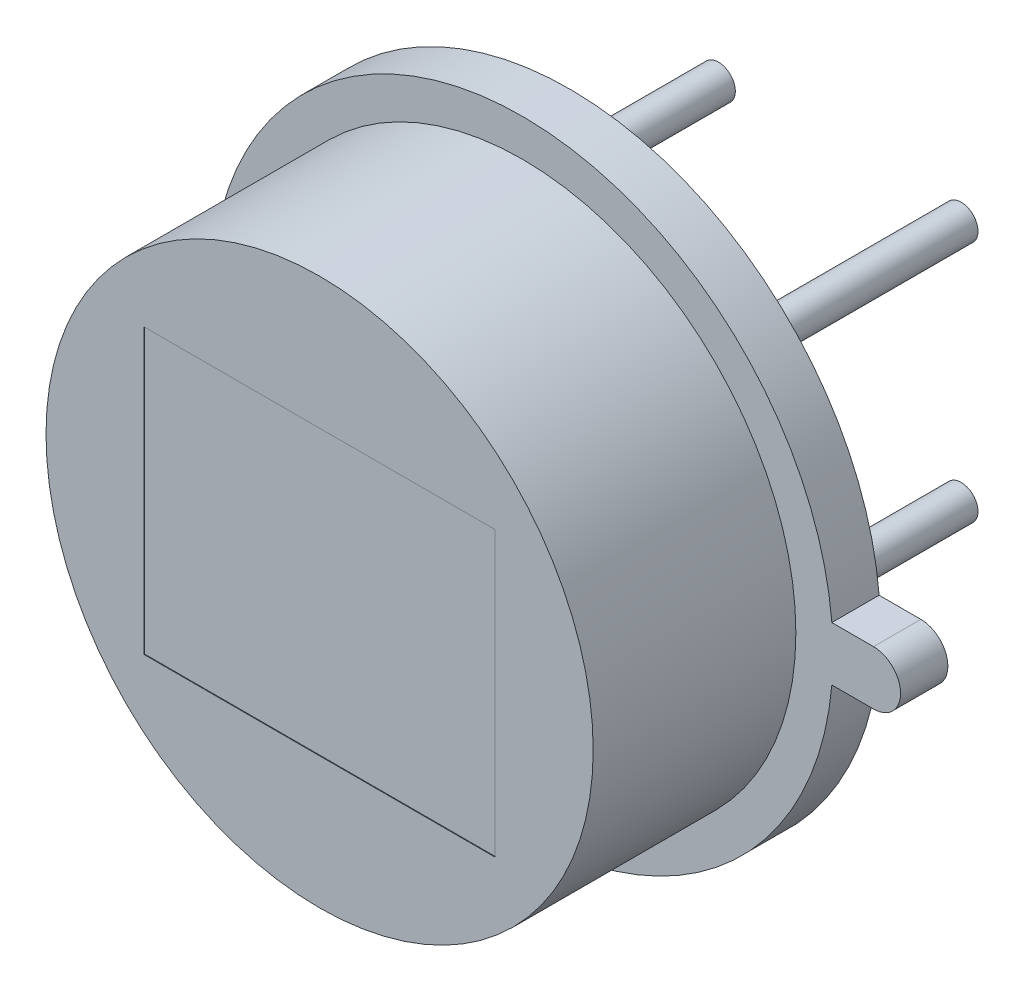
SolidWorks part; units mm, degrees
other "Детальный элемент1"
ref_plane "Спереди" through (0, 0, 0) normal (0, 0, 1) x (1, 0, 0)
ref_plane "Сверху" through (0, 0, 0) normal (0, 1, 0) x (1, 0, 0)
ref_plane "Справа" through (0, 0, 0) normal (1, 0, 0) x (0, 0, -1)
sketch "Эскиз1" plane through (0, 0, 0) normal (0, 0, 1) x (1, 0, 0)
  line L2 (5.2, 0.4) -> (4.5826, 0.4)
  line L4 (5.2, -0.4) -> (4.5826, -0.4)
  arc A1 (5.2, -0.4) -> (5.2, 0.4) centre (5.2, 0) ccw
  arc A3 (4.5826, 0.4) -> (4.5826, -0.4) centre (0, 0) ccw
  point P4 (0, 0)
  point P5 (0, 0)
  point P9 (0, 0)
  dimension "D1" = 4.6
  dimension "D2" = 0.8
  dimension "D3" = 5.2
extrude "Бобышка-Вытянуть1" add sketch "Эскиз1" along normal blind 0.7
sketch "Эскиз2" plane through (0, 0, 0.7) normal (0, 0, 1) x (1, 0, 0)
  circle A0 centre (0, 0) radius 4.05
  dimension "D1" = 8.1
extrude "Бобышка-Вытянуть2" add sketch "Эскиз2" along normal blind 3
sketch "Эскиз3" plane through (0, 0, 3.7) normal (0, 0, 1) x (1, 0, 0)
  line L1 (-2.6, -2.1) -> (2.6, -2.1)
  line L2 (-2.6, -2.1) -> (-2.6, 2.1)
  line L3 (-2.6, 2.1) -> (2.6, 2.1)
  line L4 (2.6, -2.1) -> (2.6, 2.1)
  line L5 (-2.6, -2.1) -> (2.6, 2.1) construction
  line L6 (-2.6, 2.1) -> (2.6, -2.1) construction
  point P0 (0, 0)
  dimension "D1" = 5.2
  dimension "D2" = 4.2
extrude "Вырез-Вытянуть1" cut sketch "Эскиз3" against normal blind 0.01
sketch "Эскиз4" plane through (0, 0, 0) normal (0, 0, 1) x (1, 0, 0)
  circle A0 centre (1.796, -1.796) radius 0.25
  circle A1 centre (1.796, 1.796) radius 0.25
  circle A2 centre (-1.796, 1.796) radius 0.25
  circle A3 centre (-1.796, -1.796) radius 0.25
  point P8 (0, 0)
  point P9 (0, 0)
  point P10 (0, 0)
  point P11 (0, 0)
  point P12 (0, 0)
  point P16 (0, 0)
  point P17 (-0.1374, 0.4304)
  point P18 (-0.0782, 0.0392)
  dimension "D1" = 0.5
  dimension "D2" = 0.5
  dimension "D3" = 0.5
  dimension "D4" = 0.5
  dimension "D5" = 1.796
  dimension "D6" = 1.796
  dimension "D7" = 1.796
  dimension "D8" = 1.796
extrude "Бобышка-Вытянуть3" add sketch "Эскиз4" against normal blind 4
